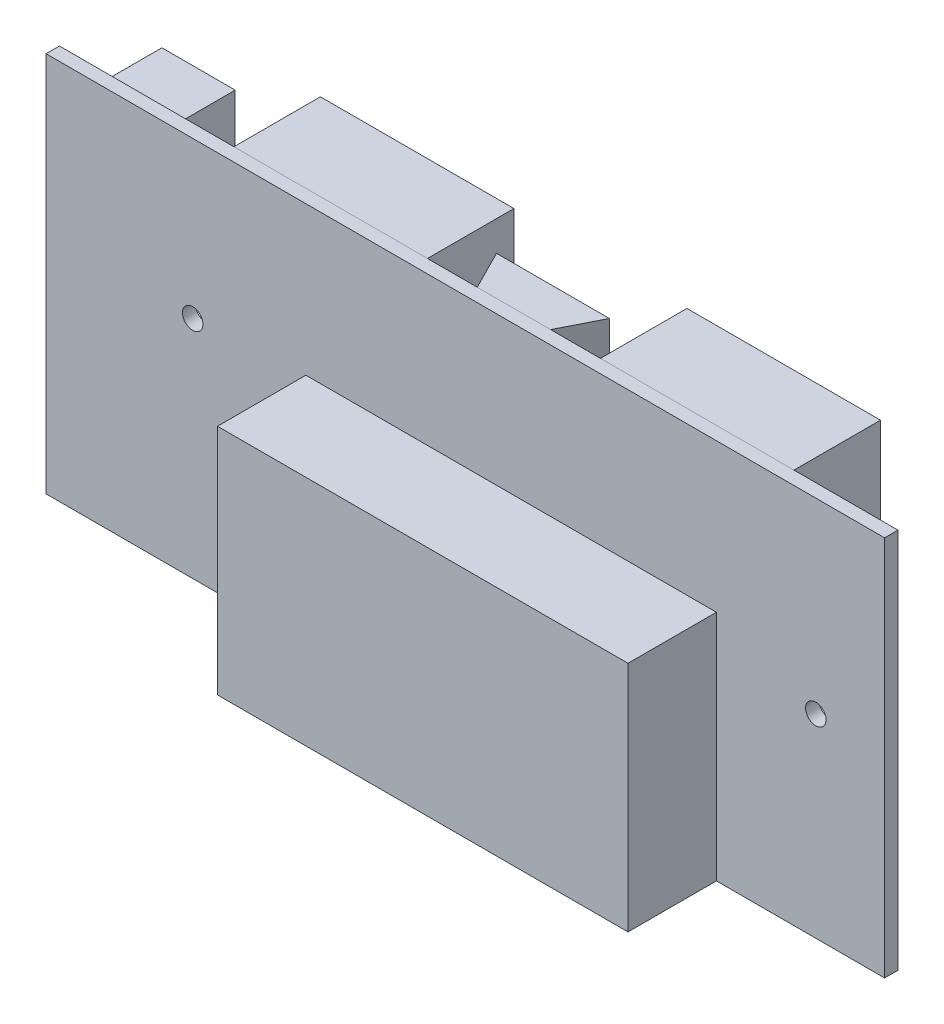
SolidWorks part; units mm, degrees
ref_plane "Спереди" through (0, 0, 0) normal (0, 0, 1) x (1, 0, 0)
ref_plane "Сверху" through (0, 0, 0) normal (0, 1, 0) x (1, 0, 0)
ref_plane "Справа" through (0, 0, 0) normal (1, 0, 0) x (0, 0, -1)
sketch "Эскиз1" plane through (0, 0, 0) normal (0, 0, 1) x (1, 0, 0)
  line L1 (0, 0) -> (57.19, 0)
  line L2 (0, 0) -> (0, 26)
  line L3 (0, 26) -> (57.19, 26)
  line L4 (57.19, 0) -> (57.19, 26)
  dimension "D1" = 57.19
  dimension "26" = 26
extrude "Бобышка-Вытянуть1" add sketch "Эскиз1" against normal blind 0.91
sketch "Эскиз2" plane through (0, 0, 0) normal (0, 0, 1) x (1, 0, 0)
  line L0 (0, 0) -> (57.19, 0) construction
  line L1 (17.72, 0) -> (45.72, 0)
  line L2 (17.72, 0) -> (17.72, 15.87)
  line L3 (17.72, 15.87) -> (45.72, 15.87)
  line L4 (45.72, 0) -> (45.72, 15.87)
  line L5 (0, 26) -> (0, 0) construction
  dimension "D1" = 17.72
  dimension "D2" = 15.87
  dimension "D3" = 28
extrude "Бобышка-Вытянуть2" add sketch "Эскиз2" along normal blind 6.03
sketch "Эскиз3" plane through (0, 0, 0) normal (0, 0, 1) x (1, 0, 0)
  line L0 (0, 26) -> (0, 0) construction
  line L1 (0, 0) -> (17.72, 0) construction
  line L3 (45.72, 0) -> (57.19, 0) construction
  circle A0 centre (10, 15.36) radius 0.7
  circle A1 centre (52.5, 13.25) radius 0.7
  dimension "D1" = 1.4
  dimension "D2" = 1.4
  dimension "D3" = 10
  dimension "D4" = 15.36
  dimension "D5" = 42.5
  dimension "D6" = 13.25
  dimension "D7" = 2.11
extrude "Вырез-Вытянуть1" cut sketch "Эскиз3" against normal blind 3
sketch "Эскиз4" plane through (0, 26, 0) normal (0, -1, 0) x (1, 0, 0)
  line L0 (27.1761, -0.91) -> (27.1761, -3.86) construction
  line L1 (0, -0.91) -> (57.19, -0.91) construction
  line L2 (27.1761, -3.86) -> (18.5, -3.86) construction
  line L3 (25.1, -0.91) -> (36.9, -0.91) construction
  line L4 (25.1, -0.91) -> (11.9, -0.91)
  line L5 (25.1, -0.91) -> (25.1, -6.81)
  line L6 (25.1, -6.81) -> (11.9, -6.81)
  line L7 (11.9, -0.91) -> (11.9, -6.81)
  line L8 (25.1, -0.91) -> (11.9, -6.81) construction
  line L9 (25.1, -6.81) -> (11.9, -0.91) construction
  line L10 (36.9, -0.91) -> (50.1, -0.91)
  line L11 (36.9, -0.91) -> (36.9, -6.81)
  line L12 (36.9, -6.81) -> (50.1, -6.81)
  line L13 (50.1, -0.91) -> (50.1, -6.81)
  line L14 (36.9, -0.91) -> (50.1, -6.81) construction
  line L15 (36.9, -6.81) -> (50.1, -0.91) construction
  line L16 (31, -0.91) -> (31, -3.57) construction
  line L17 (33.5, -0.91) -> (28.5, -0.91)
  line L18 (28.5, -0.91) -> (27.15, -3.57)
  line L19 (27.15, -3.57) -> (34.85, -3.57)
  line L20 (33.5, -0.91) -> (34.85, -3.57)
  line L23 (25.1, -6.81) -> (36.9, -6.81) construction
  point P9 (43.5, -3.86)
  dimension "D1" = 38.2
  dimension "D2" = 13.2
  dimension "D3" = 13.2
  dimension "D4" = 11.8
  dimension "D5" = 7.7
  dimension "D6" = 2.05
  dimension "D7" = 5.9
  dimension "D8" = 11.9
  dimension "D9" = 5
  dimension "D10" = 2.66
extrude "Бобышка-Вытянуть3" add sketch "Эскиз4" along normal blind 10 separate body
sketch "Эскиз5" plane through (0, 0, 0) normal (-1, 0, 0) x (0, 0, 1)
  line L0 (-0.91, 26) -> (-0.91, 0) construction
  line L1 (-0.91, 22.4) -> (-7.9, 22.4)
  line L2 (-0.91, 22.4) -> (-0.91, 16.4)
  line L3 (-0.91, 16.4) -> (-7.9, 16.4)
  line L4 (-7.9, 22.4) -> (-7.9, 16.4)
  line L5 (-7.9, 19.4) -> (-0.91, 19.4) construction
  line L7 (-0.91, 26) -> (0, 26) construction
  dimension "D1" = 6.6
  dimension "D2" = 6.99
  dimension "D3" = 6
extrude "Бобышка-Вытянуть4" add sketch "Эскиз5" against normal blind 5 separate body
sketch "Эскиз6" plane through (0, 0, 0) normal (-1, 0, 0) x (0, 0, 1)
  line L0 (-7.9, 16.4) -> (-0.91, 22.4) construction
  line L1 (-7.9, 16.4) -> (-0.91, 16.4) construction
  line L3 (-0.91, 16.4) -> (-7.9, 22.4) construction
  line L4 (-7.9, 22.4) -> (-7.9, 16.4) construction
  line L5 (-0.91, 22.4) -> (-7.9, 22.4) construction
  line L6 (-0.91, 16.4) -> (-0.91, 22.4) construction
  circle A0 centre (-4.405, 19.4) radius 1
  dimension "D1" = 2
extrude "Бобышка-Вытянуть5" add sketch "Эскиз6" along normal blind 1
